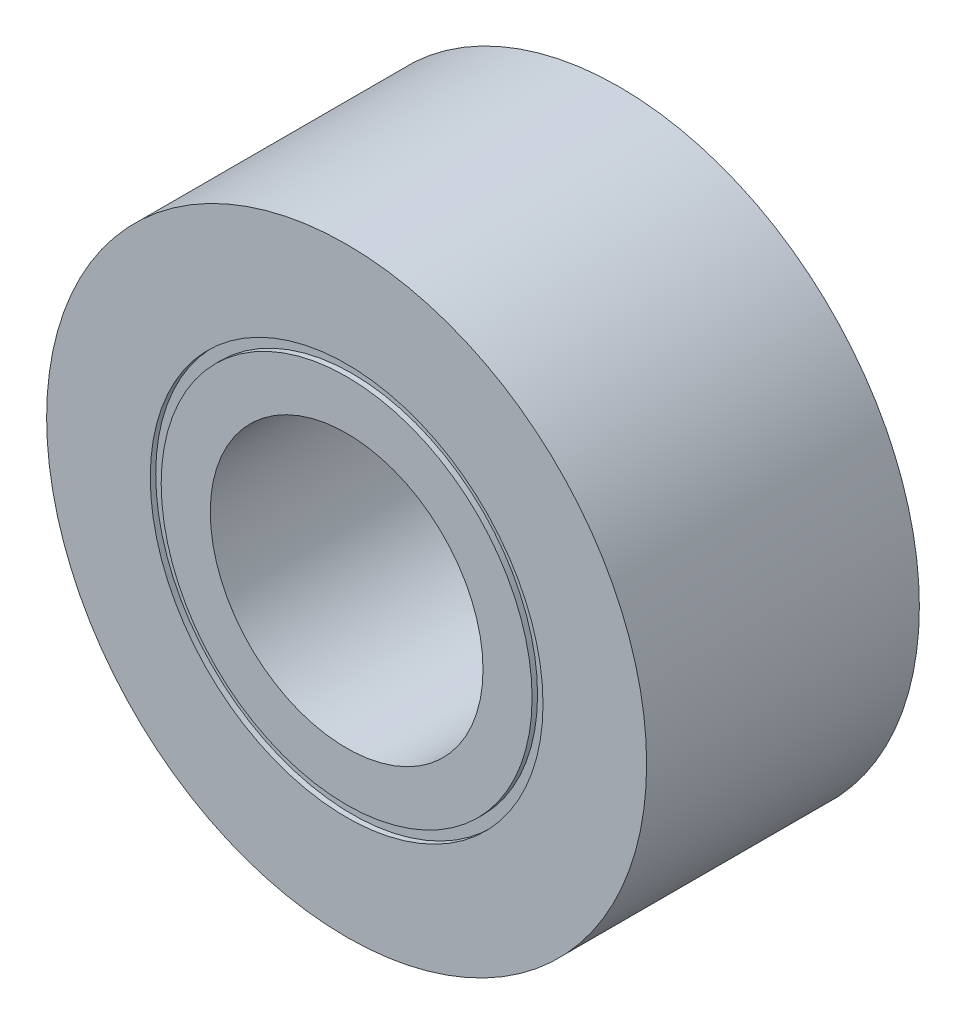
SolidWorks part; units mm, degrees
ref_plane "Front Plane" through (0, 0, 0) normal (0, 0, 1) x (1, 0, 0)
ref_plane "Top Plane" through (0, 0, 0) normal (0, 1, 0) x (1, 0, 0)
ref_plane "Right Plane" through (0, 0, 0) normal (1, 0, 0) x (0, 0, -1)
sketch "Sketch1" plane through (0, 0, 0) normal (0, 0, 1) x (1, 0, 0)
  circle A0 centre (0, 0) radius 2.5
  circle A1 centre (0, 0) radius 5.5
  dimension "D1" = 11
  dimension "D2" = 5
extrude "Boss-Extrude1" add sketch "Sketch1" along normal blind 5
sketch "Sketch2" plane through (0, 0, 5) normal (0, 0, 1) x (1, 0, 0)
  circle A0 centre (0, 0) radius 3.4
  circle A1 centre (0, 0) radius 3.6
  dimension "D1" = 6.8
  dimension "D2" = 0.2
extrude "Cut-Extrude1" cut sketch "Sketch2" against normal blind 0.1
sketch "Sketch3" plane through (0, 0, 0) normal (0, 0, -1) x (-1, 0, 0)
  circle A0 centre (0, 0) radius 3.4
  circle A3 centre (0, 0) radius 3.8
  circle A4 centre (0, 0) radius 3.8
  dimension "D1" = 6.8
  dimension "D2" = 0.2
extrude "Cut-Extrude2" cut sketch "Sketch3" against normal blind 0.1
